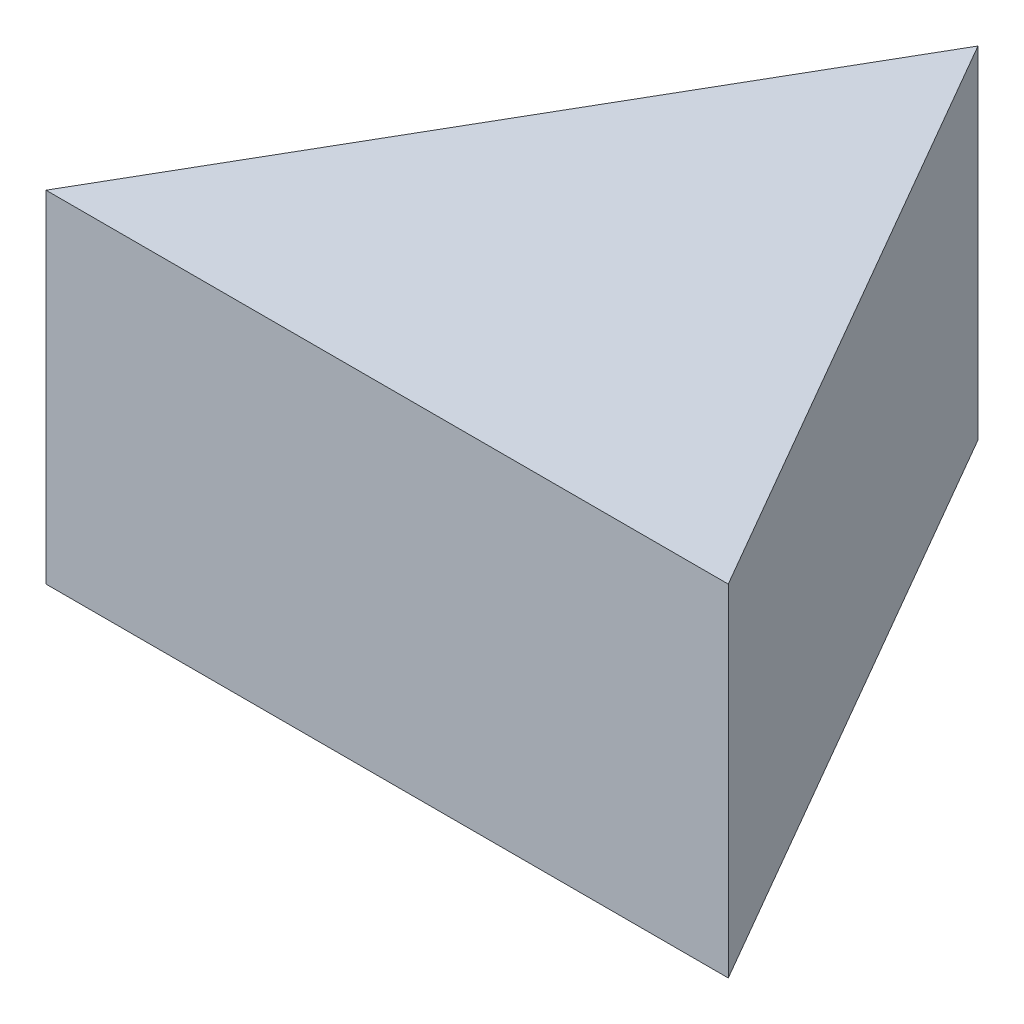
SolidWorks part; units mm, degrees
ref_plane "Front Plane" through (0, 0, 0) normal (0, 0, 1) x (1, 0, 0)
ref_plane "Top Plane" through (0, 0, 0) normal (0, 1, 0) x (1, 0, 0)
ref_plane "Right Plane" through (0, 0, 0) normal (1, 0, 0) x (0, 0, -1)
sketch "Sketch1" plane through (0, 0, 0) normal (0, 1, 0) x (1, 0, 0)
  line L0 (0, 0) -> (5, 8.6603)
  line L1 (5, 8.6603) -> (10, 0)
  line L2 (10, 0) -> (0, 0)
  dimension "D1" = 10
extrude "Boss-Extrude1" add sketch "Sketch1" along normal blind 5
